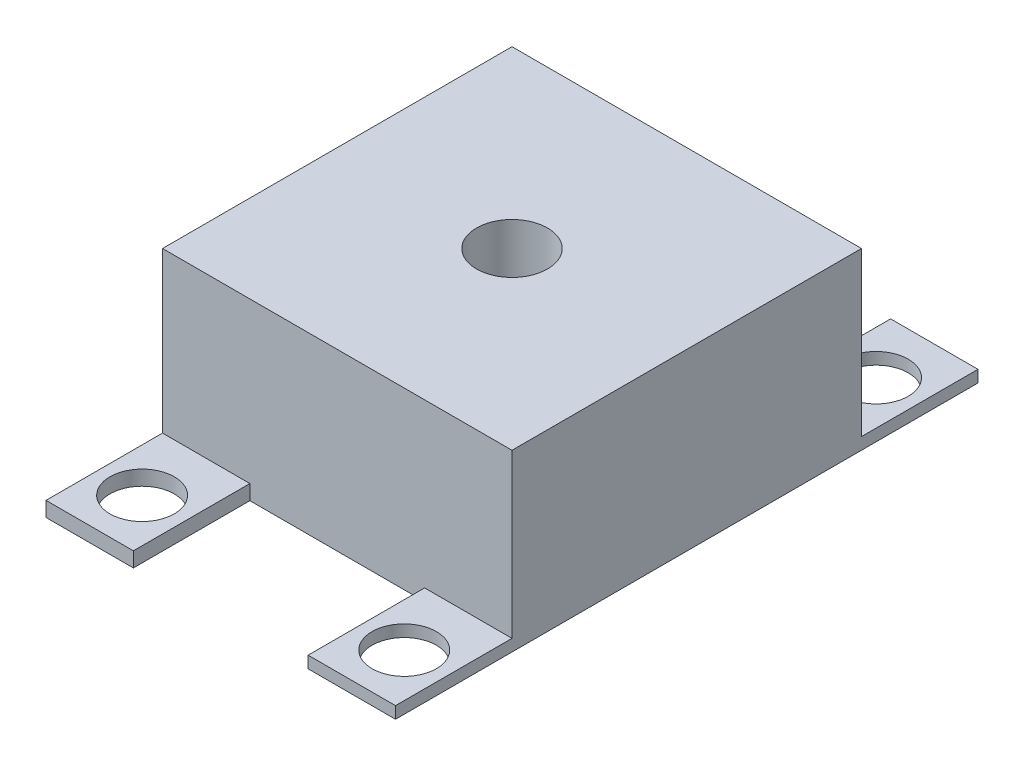
SolidWorks part; units mm, degrees
ref_plane "Front Plane" through (0, 0, 0) normal (0, 0, 1) x (1, 0, 0)
ref_plane "Top Plane" through (0, 0, 0) normal (0, 1, 0) x (1, 0, 0)
ref_plane "Right Plane" through (0, 0, 0) normal (1, 0, 0) x (0, 0, -1)
sketch "Sketch2" plane through (0, 0, 0) normal (0, 1, 0) x (1, 0, 0)
  line L1 (-15, 15) -> (15, 15)
  line L2 (-15, 15) -> (-15, -15)
  line L3 (-15, -15) -> (15, -15)
  line L4 (15, 15) -> (15, -15)
  line L5 (-15, 15) -> (15, -15) construction
  line L6 (-15, -15) -> (15, 15) construction
  point P0 (0, 0)
  dimension "D1" = 30
  dimension "D2" = 30
extrude "Boss-Extrude1" add sketch "Sketch2" along normal blind 10 contours L2 L1 L4 L3
sketch "Sketch3" plane through (0, 10, 0) normal (0, 1, 0) x (1, 0, 0)
  line L1 (-15, 15) -> (15, 15)
  line L2 (-15, 15) -> (-15, -15)
  line L3 (-15, -15) -> (15, -15)
  line L4 (15, 15) -> (15, -15)
  line L5 (-15, 15) -> (15, -15) construction
  line L6 (-15, -15) -> (15, 15) construction
  line L7 (-12.5, 12.5) -> (12.5, 12.5)
  line L8 (-12.5, 12.5) -> (-12.5, -12.5)
  line L9 (-12.5, -12.5) -> (12.5, -12.5)
  line L10 (12.5, 12.5) -> (12.5, -12.5)
  line L11 (-12.5, 12.5) -> (12.5, -12.5) construction
  line L12 (-12.5, -12.5) -> (12.5, 12.5) construction
  point P0 (0, 0)
  point P7 (0, 0)
  dimension "D1" = 25
extrude "Boss-Extrude2" add sketch "Sketch3" along normal blind 15 separate body
sketch "Sketch4" plane through (0, 25, 0) normal (0, 1, 0) x (1, 0, 0)
  line L1 (-15, 15) -> (15, 15)
  line L2 (-15, 15) -> (-15, -15)
  line L3 (-15, -15) -> (15, -15)
  line L4 (15, 15) -> (15, -15)
  line L5 (-15, 15) -> (15, -15) construction
  line L6 (-15, -15) -> (15, 15) construction
  point P0 (0, 0)
extrude "Boss-Extrude3" add sketch "Sketch4" along normal blind 15 separate body
sketch "Sketch5" plane through (0, 40, 0) normal (0, 1, 0) x (1, 0, 0)
  circle A0 centre (0, 0) radius 3.05
extrude "Cut-Extrude1" cut sketch "Sketch5" against normal up to surface (40 mm away)
delete or keep bodies "Body-Delete/Keep 2" type delete bodies bodies 102 104
sketch "Sketch6" plane through (0, 0, -15) normal (0, 0, -1) x (-1, 0, 0)
  line L1 (-15, 25) -> (-7.5, 25)
  line L2 (-15, 25) -> (-15, 26.0178)
  line L3 (-15, 26.0178) -> (-7.5, 26.0178)
  line L4 (-7.5, 25) -> (-7.5, 26.0178)
  line L5 (15, 25) -> (7.5, 25)
  line L6 (15, 25) -> (15, 26.2762)
  line L7 (15, 26.2762) -> (7.5, 26.2762)
  line L8 (7.5, 25) -> (7.5, 26.2762)
  dimension "D1" = 7.5
  dimension "D2" = 7.5
extrude "Boss-Extrude4" add sketch "Sketch6" along normal blind 10 and the other way blind 40
sketch "Sketch7" plane through (0, 26.2762, 0) normal (0, 1, 0) x (1, 0, 0)
  line L0 (-15, 20) -> (-7.5, 20) construction
  line L1 (-15, 15) -> (-15, 25) construction
  line L2 (-7.5, 15) -> (-7.5, 25) construction
  line L3 (15.1236, 20) -> (7.5761, 20) construction
  circle A0 centre (-11.25, 20) radius 2.76
  circle A1 centre (11.25, 20) radius 2.76
  circle A2 centre (11.25, -20.5) radius 2.76
  circle A3 centre (-11.25, -20.5) radius 2.76
  dimension "D1" = 5.52
  dimension "D2" = 2
  dimension "D3" = 2
extrude "Cut-Extrude2" cut sketch "Sketch7" against normal blind 10 contours A0 | A1 | A3 | A2
